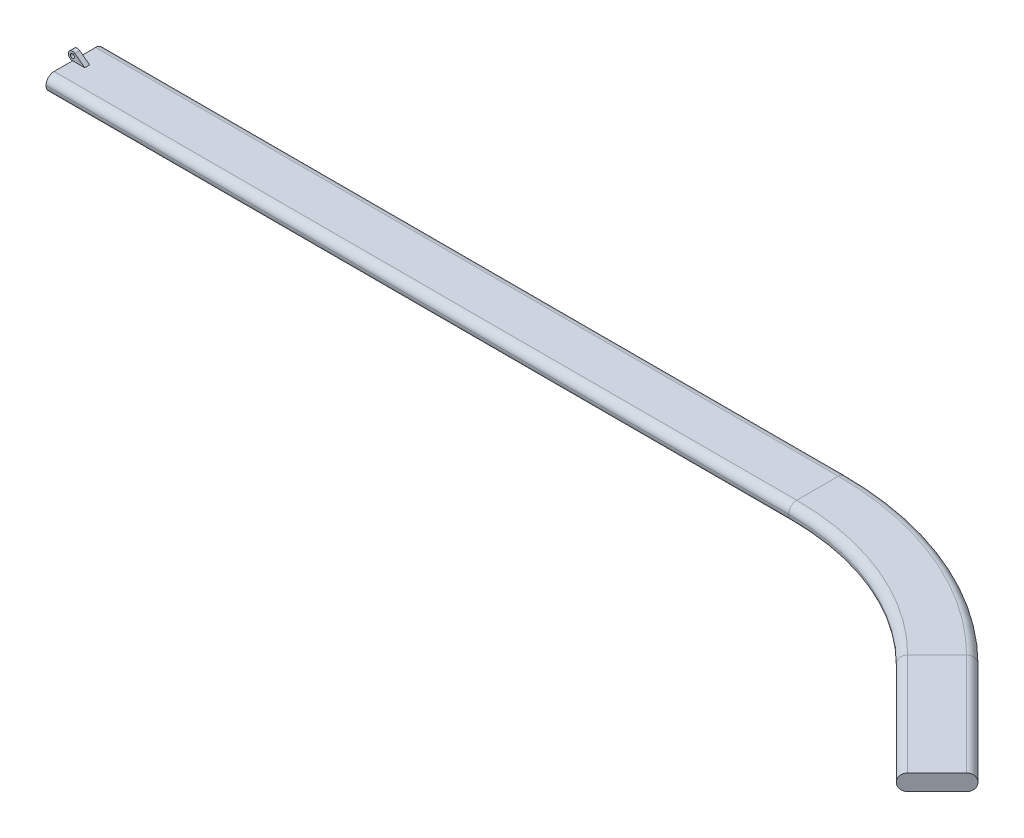
SolidWorks part; units mm, degrees
ref_plane "Front Plane" through (0, 0, 0) normal (0, 0, 1) x (1, 0, 0)
ref_plane "Top Plane" through (0, 0, 0) normal (0, 1, 0) x (1, 0, 0)
ref_plane "Right Plane" through (0, 0, 0) normal (1, 0, 0) x (0, 0, -1)
sketch "Sketch1" plane through (0, 0, 0) normal (0, 1, 0) x (1, 0, 0)
  line L0 (0, 0) -> (90, 0)
  line L1 (114.7487, -10.2513) -> (127.1309, -22.6335)
  arc A0 (90, 0) -> (114.7487, -10.2513) centre (90, -35) cw
  dimension "D1" = 35
  dimension "D3" = 135
  dimension "D2" = 90
  dimension "D4" = 45
ref_plane "Plane1" through (0, 0, 0) normal (1, 0, 0) x (0, 0, -1)
sketch "Sketch3" plane through (0, 0, 0) normal (1, 0, 0) x (0, 0, -1)
  line L1 (3.5, -0.985) -> (-3.5, -0.985)
  line L2 (3.5, -0.985) -> (3.5, 0.985)
  line L3 (3.5, 0.985) -> (-3.5, 0.985)
  line L4 (-3.5, -0.985) -> (-3.5, 0.985)
  line L5 (3.5, -0.985) -> (-3.5, 0.985) construction
  line L6 (3.5, 0.985) -> (-3.5, -0.985) construction
  point P0 (0, 0)
  dimension "D1" = 7
  dimension "D2" = 1.97
sweep "Sweep1" add profiles "Sketch3" path "Sketch1"
fillet "Fillet1" radius 0.98 12 edges at (118.465, -0.985, 18.9172) (102.0545, -0.985, 5.8978) (118.465, 0.985, 18.9172) (102.0545, 0.985, 5.8978) (123.4147, -0.985, 13.9675) (104.7333, -0.985, -0.5694) (123.4147, 0.985, 13.9675) (104.7333, 0.985, -0.5694) (45, -0.985, 3.5) (45, 0.985, 3.5) (45, -0.985, -3.5) (45, 0.985, -3.5)
ref_plane "Plane2" through (0, 0, 0.3) normal (0, 0, 1) x (1, 0, 0)
sketch "Sketch7" plane through (0, 0, 0.3) normal (0, 0, 1) x (1, 0, 0)
  line L3 (1.4873, 1.005) -> (0, 1.005)
  line L6 (0.302, 1.9035) -> (1.4873, 1.005)
  arc A4 (0.302, 1.9035) -> (0, 1.005) centre (0, 1.505) ccw
  circle A5 centre (0, 1.505) radius 0.25
extrude "Boss-Extrude1" add sketch "Sketch7" against normal blind 0.6 separate body
